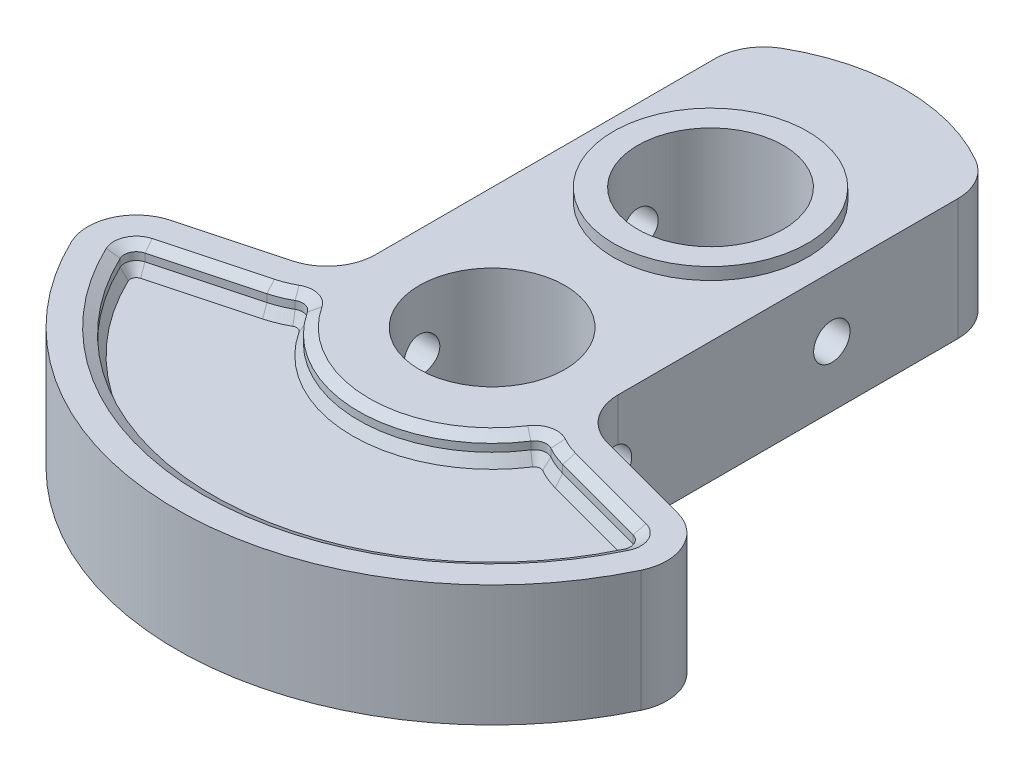
SolidWorks part; units mm, degrees
ref_plane "Front Plane" through (0, 0, 0) normal (0, 0, 1) x (1, 0, 0)
ref_plane "Top Plane" through (0, 0, 0) normal (0, 1, 0) x (1, 0, 0)
ref_plane "Right Plane" through (0, 0, 0) normal (1, 0, 0) x (0, 0, -1)
sketch "Sketch1" plane through (0, 0, 0) normal (0, 1, 0) x (1, 0, 0)
  line L0 (0, 34) -> (0, -32.7224) construction
  line L1 (-10, 30.49) -> (-10, -2.6795)
  line L2 (10, 30.49) -> (10, -2.6795)
  line L3 (0, 0) -> (-25.1141, -6.7293) construction
  line L4 (-10, 34) -> (-10, -32.7224) construction
  line L5 (10, 34) -> (10, -32.7224) construction
  line L6 (0, 0) -> (25.1141, -6.7293) construction
  line L9 (-10, -2.6795) -> (-25.1141, -6.7293)
  line L10 (10, -2.6795) -> (25.1141, -6.7293)
  arc A0 (10, 30.49) -> (-10, 30.49) centre (0, 18) ccw
  arc A2 (-25.1141, -6.7293) -> (25.1141, -6.7293) centre (0, 0) ccw
  dimension "D2" = 32
  dimension "D5" = 26
  dimension "D1" = 18
  dimension "D6" = 75
  dimension "D7" = 75
  dimension "D3" = 10
  dimension "D4" = 10
extrude "Boss-Extrude1" add sketch "Sketch1" along normal mid plane 10
fillet "Fillet1" radius 4 6 edges at (-10, 0, 2.6795) (-25.1141, 0, 6.7293) (25.1141, 0, 6.7293) (10, 0, 2.6795) (-10, 0, -30.49) (10, 0, -30.49)
sketch "Sketch2" plane through (0, -5, 0) normal (0, -1, 0) x (1, 0, 0)
  circle A0 centre (0, 0) radius 8
  dimension "D1" = 16
extrude "Boss-Extrude2" add sketch "Sketch2" along normal blind 1
sketch "Sketch3" plane through (0, 5, 0) normal (0, 1, 0) x (1, 0, 0)
  circle A0 centre (0, 18) radius 8
  point P2 (0, 0)
  dimension "D1" = 16
  dimension "D2" = 18
extrude "Boss-Extrude3" add sketch "Sketch3" along normal blind 1
sketch "Sketch4" plane through (0, -6, 0) normal (0, -1, 0) x (1, 0, 0)
  circle A0 centre (0, 0) radius 6
  circle A1 centre (0, -18) radius 6
  dimension "D1" = 12
  dimension "D2" = 12
extrude "Cut-Extrude1" cut sketch "Sketch4" against normal through all
sketch "Sketch5" plane through (0, 5, 0) normal (0, 1, 0) x (1, 0, 0)
  line L6 (12.1883, -6.3717) -> (20.1197, -8.4969)
  line L7 (-20.1197, -8.4969) -> (-12.1883, -6.3717)
  line L8 (12.1883, -6.3717) -> (20.1197, -8.4969)
  line L9 (-20.1197, -8.4969) -> (-12.1883, -6.3717)
  arc A0 (10, 0.3898) -> (12.9647, -3.4739) centre (14, 0.3898) ccw construction
  arc A10 (-9.2082, -6.0173) -> (9.2082, -6.0173) centre (0, 0) ccw
  arc A11 (9.2082, -6.0173) -> (10.5397, -5.6951) centre (10.0453, -6.5644) cw
  arc A12 (-9.2082, -6.0173) -> (-10.5397, -5.6951) centre (-10.0453, -6.5644) ccw
  arc A15 (7, 0.3898) -> (12.1883, -6.3717) centre (14, 0.3898) ccw
  arc A16 (20.7637, -9.8929) -> (20.1197, -8.4969) centre (19.8609, -9.4628) ccw
  arc A17 (-12.1883, -6.3717) -> (-7, 0.3898) centre (-14, 0.3898) ccw
  arc A18 (-20.1197, -8.4969) -> (-20.7637, -9.8929) centre (-19.8609, -9.4628) ccw
  arc A19 (-20.7637, -9.8929) -> (20.7637, -9.8929) centre (0, 0) ccw
  arc A20 (10.5397, -5.6951) -> (12.1883, -6.3717) centre (14, 0.3898) ccw
  arc A21 (20.7637, -9.8929) -> (20.1197, -8.4969) centre (19.8609, -9.4628) ccw
  arc A22 (-12.1883, -6.3717) -> (-10.5397, -5.6951) centre (-14, 0.3898) ccw
  arc A23 (-20.1197, -8.4969) -> (-20.7637, -9.8929) centre (-19.8609, -9.4628) ccw
  arc A24 (-20.7637, -9.8929) -> (20.7637, -9.8929) centre (0, 0) ccw
  point P3 (10.8266, -2.0452)
  dimension "D2" = 22
  dimension "D3" = 1
  dimension "D1" = 3
extrude "Cut-Extrude2" cut sketch "Sketch5" against normal blind 2
chamfer "Chamfer1" distance 0.5 angle 60 20 edges at (11.3424, 3, 6.0861) (9.8101, 3, 5.5924) (16.154, 3, 7.4343) (0, 3, 11) (20.7689, 3, 9.044) (-9.8101, 3, 5.5924) (0, 3, 23) (-11.3424, 3, 6.0861) (-20.7689, 3, 9.044) (-16.154, 3, 7.4343) (11.3424, 5, 6.0861) (9.8101, 5, 5.5924) (16.154, 5, 7.4343) (0, 5, 11) (20.7689, 5, 9.044) (-9.8101, 5, 5.5924) (0, 5, 23) (-11.3424, 5, 6.0861) (-20.7689, 5, 9.044) (-16.154, 5, 7.4343)
mirror "Mirror1" about plane through (0, 0, 0) normal (0, 1, 0) of "Cut-Extrude2", "Chamfer1"
sketch "Sketch6" plane through (0, 0, 0) normal (1, 0, 0) x (0, 0, -1)
  circle A0 centre (0, 0) radius 1.5
  circle A1 centre (18, 0) radius 1.5
  dimension "D2" = 3
  dimension "D3" = 3
  dimension "D1" = 18
extrude "Cut-Extrude3" cut sketch "Sketch6" against normal through all both and the other way through all
